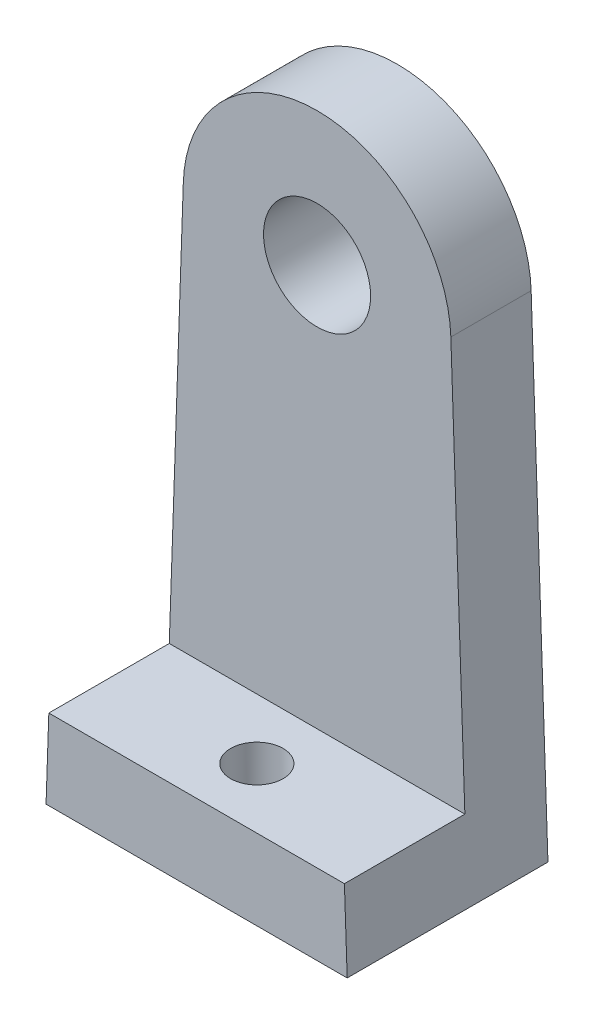
SolidWorks part; units mm, degrees
material "Gray Cast Iron"
ref_plane "Front Plane" through (0, 0, 0) normal (0, 0, 1) x (1, 0, 0)
ref_plane "Top Plane" through (0, 0, 0) normal (0, 1, 0) x (1, 0, 0)
ref_plane "Right Plane" through (0, 0, 0) normal (1, 0, 0) x (0, 0, -1)
sketch "Sketch1" plane through (0, 0, 0) normal (0, 0, 1) x (1, 0, 0)
  line L0 (-14.2875, 0) -> (14.2875, 0)
  line L1 (14.2875, 0) -> (12.6924, 46.1586)
  line L2 (-12.6924, 46.1586) -> (-14.2875, 0)
  arc A0 (12.6924, 46.1586) -> (-12.6924, 46.1586) centre (0, 45.72) ccw
extrude "Boss-Extrude1" add sketch "Sketch1" along normal mid plane 7.62
sketch "Sketch2" plane through (0, 0, 0) normal (0, 0, 1) x (1, 0, 0)
  line L0 (-14.2875, 0) -> (14.2875, 0)
  line L1 (14.2875, 0) -> (14.0242, 7.62)
  line L2 (14.0242, 7.62) -> (-14.0242, 7.62)
  line L3 (-14.0242, 7.62) -> (-14.2875, 0)
extrude "Boss-Extrude2" add sketch "Sketch2" along normal blind 11.43 from offset 3.81
sketch "Sketch3" plane through (0, 0, 0) normal (0, 0, 1) x (1, 0, 0)
  circle A0 centre (0, 45.72) radius 5.08
  dimension "D1" = 10.16
extrude "Cut-Extrude1" cut sketch "Sketch3" against normal mid plane 40
sketch "Sketch4" plane through (0, 0, 0) normal (0, 1, 0) x (1, 0, 0)
  circle A0 centre (0, -9.525) radius 2.4892
  dimension "D1" = 4.9784
extrude "Cut-Extrude2" cut sketch "Sketch4" against normal mid plane 40
